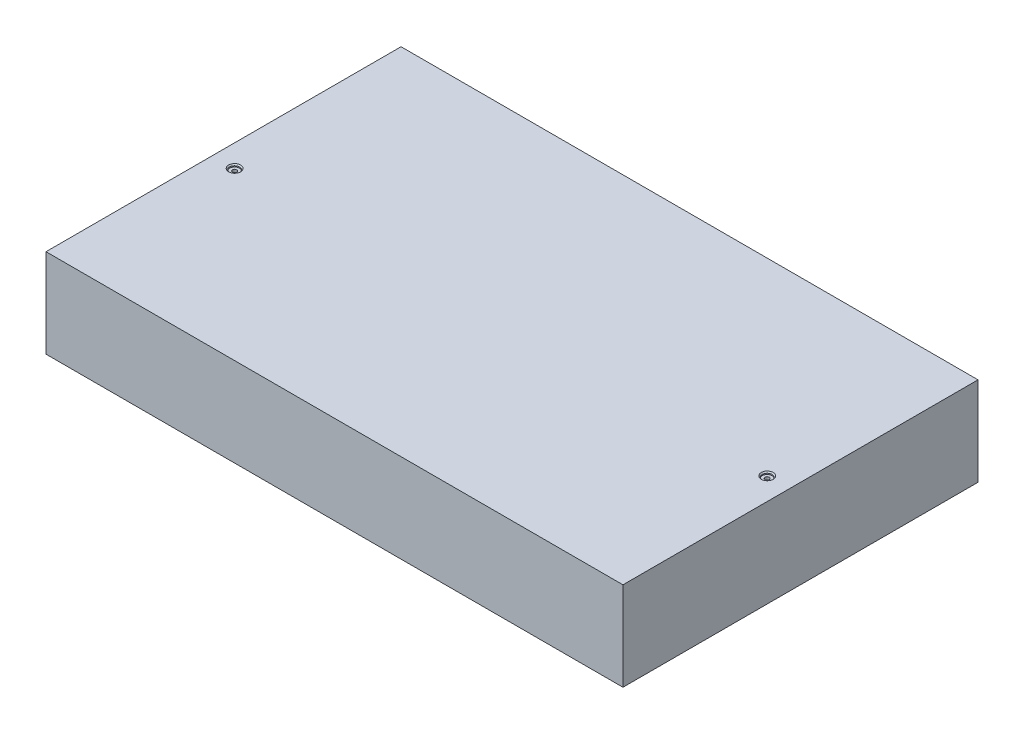
SolidWorks part; units mm, degrees
ref_plane "Front Plane" through (0, 0, 0) normal (0, 0, 1) x (1, 0, 0)
ref_plane "Top Plane" through (0, 0, 0) normal (0, 1, 0) x (1, 0, 0)
ref_plane "Right Plane" through (0, 0, 0) normal (1, 0, 0) x (0, 0, -1)
sketch "Sketch1" plane through (0, 0, 0) normal (0, 1, 0) x (1, 0, 0)
  line L1 (0, 0) -> (330.2, 0)
  line L2 (0, 0) -> (0, 203.2)
  line L3 (0, 203.2) -> (330.2, 203.2)
  line L4 (330.2, 0) -> (330.2, 203.2)
  dimension "D1" = 203.2
  dimension "D2" = 330.2
extrude "Boss-Extrude1" add sketch "Sketch1" along normal blind 50.8
sketch "Sketch3" plane through (0, 0, 0) normal (0, -1, 0) x (1, 0, 0)
  line L70 (330.2, 0) -> (330.2, -203.2) construction
  line L72 (330.2, -104.9414) -> (330.2, -104.2379)
  line L74 (279.4, -104.9414) -> (279.4, -104.2379)
  line L76 (50.8, -21.934) -> (279.4, -21.934)
  line L77 (50.8, -21.934) -> (50.8, -181.266)
  line L78 (50.8, -181.266) -> (279.4, -181.266)
  line L79 (279.4, -21.934) -> (279.4, -181.266)
  line L80 (50.8, -21.934) -> (279.4, -181.266) construction
  line L81 (50.8, -181.266) -> (279.4, -21.934) construction
  point P8 (165.1, -101.6)
extrude "Cut-Extrude1" cut sketch "Sketch3" against normal blind 12.7 contours L79 L76 L77 L78 L74
hole_wizard "CBORE for #2 Binding Head Machine Screw1" positions "3DSketch3" profile "Sketch5" counterbore size "#2" standard "ANSI Inch" end condition through all
sketch3d "3DSketch3"
  point P0 (12.7009, 50.8, -95.25)
  point P2 (317.5, 50.8, -95.25)
  point P32 (0, 0, 0)
  point P33 (317.5, 50.8, -95.25)
  point P34 (0, 0, 0)
  point P35 (12.8026, 50.8, -95.25)
  point P36 (0, 0, 0)
  point P37 (0, 0, 0)
  point P38 (12.7009, 50.8, -95.25)
sketch "Sketch5" plane through (12.7009, 50.8, -95.25) normal (1, 0, 0) x (0, 0, 1)
  line L0 (0, 0) -> (0, 50.8)
  line L1 (0, 50.8) -> (1.2192, 50.8)
  line L3 (1.2192, 50.8) -> (1.2192, 1.27)
  line L4 (2.7788, 1.27) -> (1.2192, 1.27)
  line L5 (2.7788, 1.27) -> (2.7788, 0.635)
  line L6 (2.7788, 0.635) -> (3.4138, 0)
  line L7 (3.4138, 0) -> (0, 0)
  line L8 (-2.7788, 0.635) -> (-3.4138, 0) construction
  line L11 (0, -6.35) -> (0, 107.95) construction
  dimension "Thru Hole Dia." = 2.4384
  dimension "Thru Hole Depth" = 50.8
  dimension "C'Bore Dia." = 5.5575
  dimension "C'Bore Depth" = 1.27
  dimension "Near C'Sink Dia." = 6.8275
  dimension "Near C'Sink Angle" = 90
